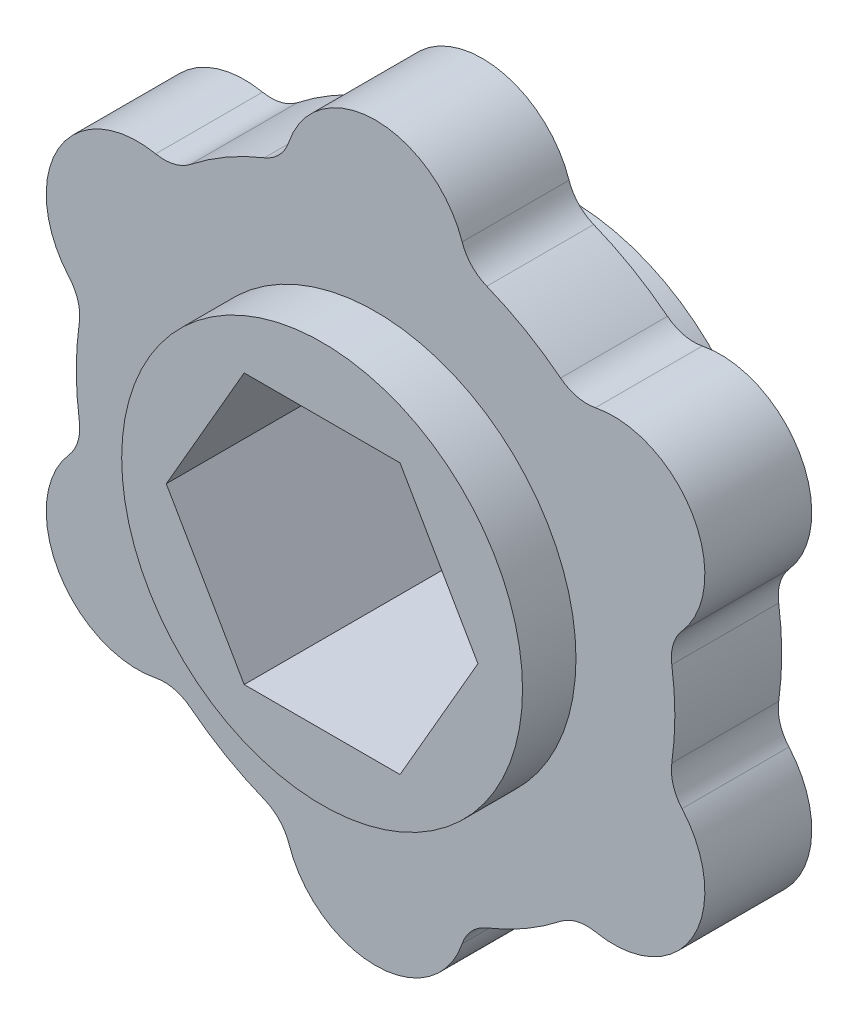
SolidWorks part; units mm, degrees
material "PET"
ref_plane "Front Plane" through (0, 0, 0) normal (0, 0, 1) x (1, 0, 0)
ref_plane "Top Plane" through (0, 0, 0) normal (0, 1, 0) x (1, 0, 0)
ref_plane "Right Plane" through (0, 0, 0) normal (1, 0, 0) x (0, 0, -1)
sketch "Sketch5" plane through (0, 0, 0) normal (0, 0, 1) x (1, 0, 0)
  line L0 (0, 0) -> (0, 13.0556) construction
  circle A0 centre (0, 0) radius 14.224
  circle A1 centre (0, 0) radius 17.399 construction
  arc A2 (-4.3147, 13.5538) -> (4.3147, 13.5538) centre (0, 13.0556) cw
  arc A3 (9.5806, 10.5136) -> (13.8953, 3.0402) centre (11.3065, 6.5278) cw
  arc A4 (13.8953, -3.0402) -> (9.5806, -10.5136) centre (11.3065, -6.5278) cw
  arc A5 (4.3147, -13.5538) -> (-4.3147, -13.5538) centre (0, -13.0556) cw
  arc A6 (-9.5806, -10.5136) -> (-13.8953, -3.0402) centre (-11.3065, -6.5278) cw
  arc A7 (-13.8953, 3.0402) -> (-9.5806, 10.5136) centre (-11.3065, 6.5278) cw
  point P24 (0, 0)
  dimension "D1" = 28.448
  dimension "D2" = 34.798
  dimension "D3" = 4.3434
  dimension "D4" = 6
extrude "Boss-Extrude2" add sketch "Sketch5" along normal blind 5.08 contours A7 A0 | A2 A0 | A3 A0 | A4 A0 | A5 A0 | A6 A0
fillet "Fillet1" radius 2.032 12 edges at (-13.8953, 3.0402, 2.54) (-9.5806, 10.5136, 2.54) (-4.3147, 13.5538, 2.54) (4.3147, 13.5538, 2.54) (9.5806, 10.5136, 2.54) (13.8953, 3.0402, 2.54) (13.8953, -3.0402, 2.54) (9.5806, -10.5136, 2.54) (4.3147, -13.5538, 2.54) (-4.3147, -13.5538, 2.54) (-9.5806, -10.5136, 2.54) (-13.8953, -3.0402, 2.54)
sketch "Sketch6" plane through (0, 0, 5.08) normal (0, 0, 1) x (1, 0, 0)
  line L1 (7.4057, 0) -> (3.7028, 6.4135)
  line L2 (3.7028, 6.4135) -> (-3.7028, 6.4135)
  line L3 (-3.7028, 6.4135) -> (-7.4057, 0)
  line L4 (-7.4057, 0) -> (-3.7028, -6.4135)
  line L5 (-3.7028, -6.4135) -> (3.7028, -6.4135)
  line L6 (3.7028, -6.4135) -> (7.4057, 0)
  circle A0 centre (0, 0) radius 6.4135 construction
  dimension "D1" = 12.827
extrude "Cut-Extrude1" cut sketch "Sketch6" against normal through all
sketch "Sketch7" plane through (0, 0, 0) normal (0, 0, -1) x (-1, 0, 0)
  line L0 (-7.4057, 0) -> (-3.7028, 6.4135) construction
  line L1 (-3.7028, -6.4135) -> (-7.4057, 0) construction
  line L2 (3.7028, -6.4135) -> (-3.7028, -6.4135) construction
  line L3 (7.4057, 0) -> (3.7028, -6.4135) construction
  line L4 (3.7028, 6.4135) -> (7.4057, 0) construction
  line L5 (-3.7028, 6.4135) -> (3.7028, 6.4135) construction
  line L6 (-7.4057, 0) -> (-3.7028, 6.4135)
  line L7 (-3.7028, -6.4135) -> (-7.4057, 0)
  line L8 (3.7028, -6.4135) -> (-3.7028, -6.4135)
  line L9 (7.4057, 0) -> (3.7028, -6.4135)
  line L10 (3.7028, 6.4135) -> (7.4057, 0)
  line L11 (-3.7028, 6.4135) -> (3.7028, 6.4135)
  circle A0 centre (0, 0) radius 9.525
  dimension "D1" = 19.05
extrude "Boss-Extrude3" add sketch "Sketch7" along normal blind 4.143 and the other way blind 7.62
